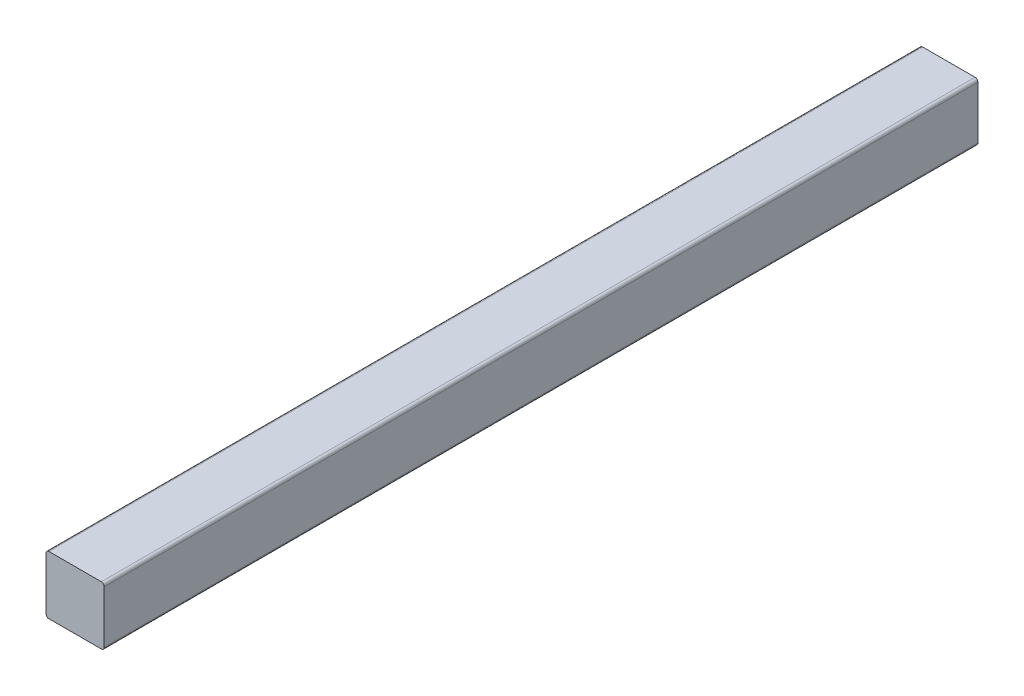
SolidWorks part; units mm, degrees
ref_plane "Front Plane" through (0, 0, 0) normal (0, 0, 1) x (1, 0, 0)
ref_plane "Top Plane" through (0, 0, 0) normal (0, 1, 0) x (1, 0, 0)
ref_plane "Right Plane" through (0, 0, 0) normal (1, 0, 0) x (0, 0, -1)
sketch "Sketch1" plane through (0, 0, 0) normal (0, 0, 1) x (1, 0, 0)
  line L1 (1, 0) -> (19, 0)
  line L2 (0, 1) -> (0, 19)
  line L3 (1, 20) -> (19, 20)
  line L4 (20, 1) -> (20, 19)
  arc A0 (19, 0) -> (20, 1) centre (19, 1) ccw
  arc A1 (19, 20) -> (20, 19) centre (19, 19) cw
  arc A2 (0, 19) -> (1, 20) centre (1, 19) cw
  arc A3 (1, 0) -> (0, 1) centre (1, 1) cw
  point P7 (20, 0)
  point P12 (0, 20)
  point P15 (0, 0)
  dimension "D3" = 1
  dimension "D1" = 20
  dimension "D2" = 20
extrude "Boss-Extrude1" add sketch "Sketch1" along normal blind 300
